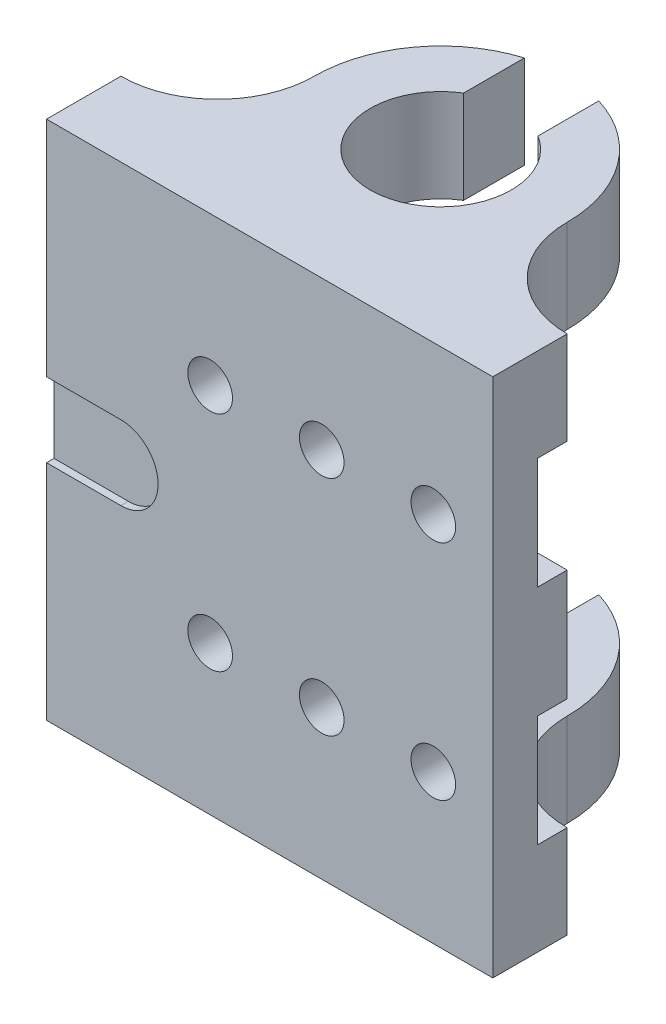
SolidWorks part; units mm, degrees
ref_plane "前视基准面" through (0, 0, 0) normal (0, 0, 1) x (1, 0, 0)
ref_plane "上视基准面" through (0, 0, 0) normal (0, 1, 0) x (1, 0, 0)
ref_plane "右视基准面" through (0, 0, 0) normal (1, 0, 0) x (0, 0, -1)
sketch "草图1" plane through (0, 0, 0) normal (0, 0, 1) x (1, 0, 0)
  line L1 (-30, 35) -> (30, 35)
  line L2 (-30, 35) -> (-30, -35)
  line L3 (-30, -35) -> (30, -35)
  line L4 (30, 35) -> (30, -35)
  line L5 (-30, 35) -> (30, -35) construction
  line L6 (-30, -35) -> (30, 35) construction
  point P0 (0, 0)
  dimension "D1" = 60
  dimension "D2" = 70
extrude "凸台-拉伸1" add sketch "草图1" along normal blind 10
sketch "草图2" plane through (0, 0, 10) normal (0, 0, 1) x (1, 0, 0)
  line L0 (0, 0) -> (24.7398, 0) construction
  line L1 (0, 15) -> (30, 15) construction
  line L3 (5.5, 0) -> (-5.5, 0) construction
  line L4 (-2.1573, -15) -> (27.8427, -15) construction
  circle A0 centre (-8, 15) radius 3
  circle A1 centre (7, 15) radius 3
  circle A2 centre (-8, -15) radius 3
  circle A3 centre (7, -15) radius 3
  circle A6 centre (22, 15) radius 3
  circle A7 centre (22, -15) radius 3
  dimension "D6" = 6
  dimension "D7" = 6
  dimension "D8" = 6
  dimension "D9" = 6
  dimension "D14" = 6
  dimension "D15" = 6
  dimension "D1" = 15
  dimension "D2" = 15
  dimension "D3" = 15
  dimension "D12" = 15
  dimension "D13" = 15
extrude "切除-拉伸1" cut sketch "草图2" against normal through all
sketch "草图3" plane through (0, 0, 0) normal (0, 0, -1) x (-1, 0, 0)
  line L0 (8, 22.5) -> (-30, 22.5)
  line L1 (8, 7.5) -> (-30, 7.5)
  line L4 (-30, 35) -> (-30, -35)
  line L5 (-30, -35) -> (30, -35)
  line L6 (30, -35) -> (30, 35)
  line L7 (30, 35) -> (-30, 35)
  line L8 (-30, 35) -> (-30, -35)
  line L9 (-30, -35) -> (30, -35)
  line L10 (30, -35) -> (30, 35)
  line L11 (30, 35) -> (-30, 35)
  circle A0 centre (8, -15) radius 3 construction
  circle A1 centre (-7, -15) radius 3 construction
  circle A2 centre (8, 15) radius 3 construction
  circle A3 centre (-7, 15) radius 3 construction
  circle A4 centre (8, -15) radius 3
  circle A5 centre (-7, -15) radius 3
  circle A6 centre (8, 15) radius 3
  circle A7 centre (-7, 15) radius 3
  circle A8 centre (8, 15) radius 7.5
  circle M7 centre (-7, 15) radius 3
  circle M10 centre (8, 15) radius 3
  line M11 (-30, 35) -> (-30, -35)
  dimension "D2" = 15
  dimension "D1" = 0
extrude "切除-拉伸2" cut sketch "草图3" against normal blind 4 contours A8 M10 | A8 L0 L1 M11 M7
mirror "镜向1" about plane through (0, 0, 0) normal (0, 1, 0) of "切除-拉伸2"
sketch "草图4" plane through (0, 0, 10) normal (0, 0, 1) x (1, 0, 0)
  line L0 (-20, 5) -> (-30, 5)
  line L1 (-20, -5) -> (-30, -5)
  line L4 (30, -35) -> (30, 35)
  line L5 (30, 35) -> (-30, 35)
  line L6 (-30, 35) -> (-30, -35)
  line L7 (-30, -35) -> (30, -35)
  line L8 (30, -35) -> (30, 35)
  line L9 (30, 35) -> (-30, 35)
  line L10 (-30, 35) -> (-30, -35)
  line L11 (-30, -35) -> (30, -35)
  circle A0 centre (-20, 0) radius 5
  line M14 (-30, 35) -> (-30, -35)
  dimension "D2" = 10
  dimension "D3" = 10
  dimension "D1" = 0
extrude "切除-拉伸3" cut sketch "草图4" against normal blind 1 contours A0 | A0 L0 L1 M14
sketch "草图6" plane through (0, 35, 0) normal (0, 1, 0) x (1, 0, 0)
  line L0 (0, -5.5) -> (0, 5.5) construction
  line L4 (30, 0) -> (-30, 0)
  line L5 (-30, 0) -> (-30, -10)
  line L6 (-30, -10) -> (30, -10)
  line L7 (30, -10) -> (30, 0)
  line L8 (30, 0) -> (-30, 0)
  line L9 (-30, 0) -> (-30, -10)
  line L10 (-30, -10) -> (30, -10)
  line L11 (30, -10) -> (30, 0)
  arc A0 (-30, 0) -> (-17, 13) centre (-30, 13) ccw
  arc A1 (-17, 13) -> (17, 13) centre (0, 13) cw
  arc A2 (30, 0) -> (17, 13) centre (30, 13) cw
  point P8 (0, 0)
  line M5 (30, 0) -> (-30, 0)
  dimension "D2" = 13
  dimension "D1" = 0
extrude "凸台-拉伸2" add sketch "草图6" against normal blind 12.5 contours A2 A1 A0 M5
sketch "草图7" plane through (0, 35, 0) normal (0, 1, 0) x (1, 0, 0)
  line L0 (0, 22.5) -> (0, 30) construction
  line L1 (-5, 29.2481) -> (-5, 21.0777)
  line L2 (5, 29.2481) -> (5, 21.0777)
  line L3 (30, -10) -> (30, 0)
  line L4 (-30, 0) -> (-30, -10)
  line L5 (-30, -10) -> (30, -10)
  line L6 (30, -10) -> (30, 0)
  line L7 (-30, 0) -> (-30, -10)
  line L8 (-30, -10) -> (30, -10)
  circle A0 centre (0, 13) radius 9.5
  arc A3 (17, 13) -> (30, 0) centre (30, 13) ccw
  arc A4 (17, 13) -> (-17, 13) centre (0, 13) ccw
  arc A5 (-30, 0) -> (-17, 13) centre (-30, 13) ccw
  arc A6 (17, 13) -> (30, 0) centre (30, 13) ccw
  arc A7 (17, 13) -> (-17, 13) centre (0, 13) ccw
  arc A8 (-30, 0) -> (-17, 13) centre (-30, 13) ccw
  arc M12 (17, 13) -> (-17, 13) centre (0, 13) ccw
  dimension "D2" = 19
  dimension "D3" = 5
  dimension "D1" = 0
extrude "切除-拉伸4" cut sketch "草图7" against normal up to surface (12.5 mm away) contours A0 | L0 A0 L2 M12 | A0 L0 A7 L1 up to face at (2, 22.5, -4.2307)
mirror "镜向2" about plane through (0, 0, 0) normal (0, 1, 0) of "切除-拉伸4", "凸台-拉伸2"
